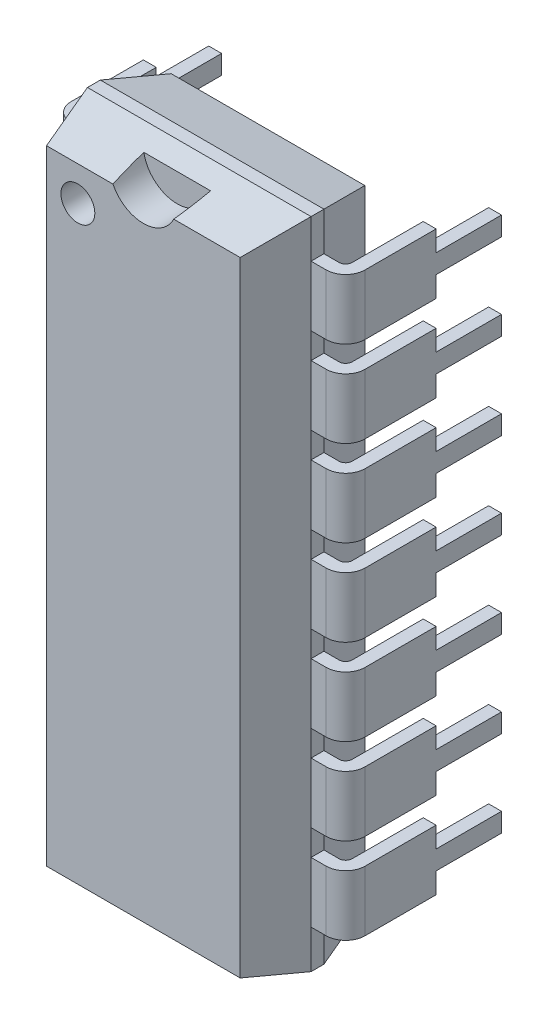
SolidWorks part; units mm, degrees
ref_plane "Спереди" through (0, 0, 0) normal (0, 0, 1) x (1, 0, 0)
ref_plane "Сверху" through (0, 0, 0) normal (0, 1, 0) x (1, 0, 0)
ref_plane "Справа" through (0, 0, 0) normal (1, 0, 0) x (0, 0, -1)
sketch "Эскиз1" plane through (0, 0, 0) normal (0, 0, 1) x (1, 0, 0)
  line L0 (8.07, 0.89) -> (8.07, -0.89) [skipped]
  line L1 (-0.19, 0.89) -> (0.19, 0.89)
  line L2 (-0.19, 0.89) -> (-0.19, -0.89)
  line L3 (-0.19, -0.89) -> (0.19, -0.89)
  line L4 (0.19, 0.89) -> (0.19, -0.89)
  line L5 (8.07, -0.89) -> (8.45, -0.89) [skipped]
  line L6 (8.45, 0.89) -> (8.45, -0.89) [skipped]
  line L7 (8.07, -1.65) -> (8.45, -1.65) [skipped]
  line L8 (-0.19, -1.65) -> (0.19, -1.65)
  line L9 (-0.19, -1.65) -> (-0.19, -3.43)
  line L10 (-0.19, -3.43) -> (0.19, -3.43)
  line L11 (0.19, -1.65) -> (0.19, -3.43)
  line L12 (8.07, -1.65) -> (8.07, -3.43) [skipped]
  line L13 (8.07, -3.43) -> (8.45, -3.43) [skipped]
  line L14 (8.45, -1.65) -> (8.45, -3.43) [skipped]
  line L15 (8.07, -4.19) -> (8.45, -4.19) [skipped]
  line L16 (-0.19, -4.19) -> (0.19, -4.19)
  line L17 (-0.19, -4.19) -> (-0.19, -5.97)
  line L18 (-0.19, -5.97) -> (0.19, -5.97)
  line L19 (0.19, -4.19) -> (0.19, -5.97)
  line L20 (8.07, -4.19) -> (8.07, -5.97) [skipped]
  line L21 (8.07, -5.97) -> (8.45, -5.97) [skipped]
  line L22 (8.45, -4.19) -> (8.45, -5.97) [skipped]
  line L23 (8.07, -6.73) -> (8.45, -6.73) [skipped]
  line L24 (-0.19, -6.73) -> (0.19, -6.73)
  line L25 (-0.19, -6.73) -> (-0.19, -8.51)
  line L26 (-0.19, -8.51) -> (0.19, -8.51)
  line L27 (0.19, -6.73) -> (0.19, -8.51)
  line L28 (8.07, -6.73) -> (8.07, -8.51) [skipped]
  line L29 (8.07, -8.51) -> (8.45, -8.51) [skipped]
  line L30 (8.45, -6.73) -> (8.45, -8.51) [skipped]
  line L31 (8.07, -9.27) -> (8.45, -9.27) [skipped]
  line L32 (-0.19, -9.27) -> (0.19, -9.27)
  line L33 (-0.19, -9.27) -> (-0.19, -11.05)
  line L34 (-0.19, -11.05) -> (0.19, -11.05)
  line L35 (0.19, -9.27) -> (0.19, -11.05)
  line L36 (8.07, -9.27) -> (8.07, -11.05) [skipped]
  line L37 (8.07, -11.05) -> (8.45, -11.05) [skipped]
  line L38 (8.45, -9.27) -> (8.45, -11.05) [skipped]
  line L39 (8.07, -11.81) -> (8.45, -11.81) [skipped]
  line L40 (-0.19, -11.81) -> (0.19, -11.81)
  line L41 (-0.19, -11.81) -> (-0.19, -13.59)
  line L42 (-0.19, -13.59) -> (0.19, -13.59)
  line L43 (0.19, -11.81) -> (0.19, -13.59)
  line L44 (8.07, -11.81) -> (8.07, -13.59) [skipped]
  line L45 (8.07, -13.59) -> (8.45, -13.59) [skipped]
  line L46 (8.45, -11.81) -> (8.45, -13.59) [skipped]
  line L47 (8.07, -14.35) -> (8.45, -14.35) [skipped]
  line L48 (-0.19, -14.35) -> (0.19, -14.35)
  line L49 (-0.19, -14.35) -> (-0.19, -16.13)
  line L50 (-0.19, -16.13) -> (0.19, -16.13)
  line L51 (0.19, -14.35) -> (0.19, -16.13)
  line L52 (8.07, -14.35) -> (8.07, -16.13) [skipped]
  line L53 (8.07, -16.13) -> (8.45, -16.13) [skipped]
  line L54 (8.45, -14.35) -> (8.45, -16.13) [skipped]
  line L56 (8.07, 0.89) -> (8.45, 0.89) [skipped]
ref_plane "Плоскость1" through (0, 0, 4.32) normal (0, 0, 1) x (1, 0, 0)
sketch "Эскиз2" plane through (0, 0, 4.32) normal (0, 0, 1) x (1, 0, 0)
  line L0 (4.13, 0.5264) -> (4.13, -12.1874) construction
  line L3 (-1.5963, -7.62) -> (10.5039, -7.62) construction
  line L7 (0.83, 2.03) -> (7.43, 2.03)
  line L8 (0.83, 2.03) -> (0.83, -17.27)
  line L9 (0.83, -17.27) -> (7.43, -17.27)
  line L10 (7.43, 2.03) -> (7.43, -17.27)
extrude "Вытянуть1" add sketch "Эскиз2" against normal blind 3.68
chamfer "Фаска1" distance 1.65 angle 15 8 edges at (4.13, -17.27, 0.64) (0.83, -7.62, 0.64) (4.13, 2.03, 0.64) (7.43, -7.62, 0.64) (4.13, -17.27, 4.32) (0.83, -7.62, 4.32) (4.13, 2.03, 4.32) (7.43, -7.62, 4.32)
sketch "Эскиз3" plane through (0, 0, 0) normal (0, 1, 0) x (1, 0, 0)
  line L0 (0, 0) -> (0, -2.1333)
  line L1 (0.3702, -2.48) -> (0.83, -2.48)
  line L2 (0.83, -2.29) -> (0.83, -2.67) construction
  arc A0 (0, -2.1333) -> (0.3702, -2.48) centre (0.3475, -2.1333) ccw
sweep "По траектории3" add profiles "Эскиз1" path "Эскиз3"
sketch "Эскиз4" plane through (0, 0, 0) normal (0, 0, 1) x (1, 0, 0)
  line L1 (8.07, 0.89) -> (8.45, 0.89)
  line L2 (8.07, 0.89) -> (8.07, -0.89)
  line L3 (8.07, -0.89) -> (8.45, -0.89)
  line L4 (8.45, 0.89) -> (8.45, -0.89)
  line L9 (8.07, -1.65) -> (8.45, -1.65)
  line L10 (8.07, -1.65) -> (8.07, -3.43)
  line L11 (8.07, -3.43) -> (8.45, -3.43)
  line L12 (8.45, -1.65) -> (8.45, -3.43)
  line L13 (8.07, -4.19) -> (8.45, -4.19)
  line L14 (8.07, -4.19) -> (8.07, -5.97)
  line L15 (8.07, -5.97) -> (8.45, -5.97)
  line L16 (8.45, -4.19) -> (8.45, -5.97)
  line L17 (8.07, -6.73) -> (8.45, -6.73)
  line L18 (8.07, -6.73) -> (8.07, -8.51)
  line L19 (8.07, -8.51) -> (8.45, -8.51)
  line L20 (8.45, -6.73) -> (8.45, -8.51)
  line L21 (8.07, -9.27) -> (8.45, -9.27)
  line L22 (8.07, -9.27) -> (8.07, -11.05)
  line L23 (8.07, -11.05) -> (8.45, -11.05)
  line L24 (8.45, -9.27) -> (8.45, -11.05)
  line L25 (8.07, -11.81) -> (8.45, -11.81)
  line L26 (8.07, -11.81) -> (8.07, -13.59)
  line L27 (8.07, -13.59) -> (8.45, -13.59)
  line L28 (8.45, -11.81) -> (8.45, -13.59)
  line L29 (8.07, -14.35) -> (8.45, -14.35)
  line L30 (8.07, -14.35) -> (8.07, -16.13)
  line L31 (8.07, -16.13) -> (8.45, -16.13)
  line L32 (8.45, -14.35) -> (8.45, -16.13)
sketch "Эскиз5" plane through (0, 0, 0) normal (0, 1, 0) x (1, 0, 0)
  line L0 (7.43, -2.48) -> (7.8737, -2.48)
  line L1 (7.43, -2.29) -> (7.43, -2.67) construction
  line L2 (8.26, -2.0937) -> (8.26, 0)
  line L3 (8.07, 0) -> (8.45, 0) construction
  arc A0 (7.8737, -2.48) -> (8.26, -2.0937) centre (7.8737, -2.0937) ccw
sweep "По траектории4" add profiles "Эскиз4" path "Эскиз5"
sketch "Эскиз6" plane through (0, 0, 4.32) normal (0, 0, 1) x (1, 0, 0)
  line L0 (0.83, 2.03) -> (7.43, 2.03) construction
  circle A0 centre (4.13, 2.03) radius 1
  circle A1 centre (2.1974, 0.5741) radius 0.5
extrude "Вырез-Вытянуть1" cut sketch "Эскиз6" against normal blind 1
sketch "Эскиз7" plane through (0, 0, 0) normal (0, 0, -1) x (-1, 0, 0)
  line L0 (-0.19, -0.89) -> (-0.19, 0.89) construction
  line L1 (-0.19, 0.28) -> (0.19, 0.28)
  line L2 (-0.19, 0.28) -> (-0.19, -0.28)
  line L3 (-0.19, -0.28) -> (0.19, -0.28)
  line L4 (0.19, 0.28) -> (0.19, -0.28)
  line L5 (-8.45, 0.28) -> (-8.07, 0.28)
  line L6 (-8.45, 0.28) -> (-8.45, -0.28)
  line L7 (-8.45, -0.28) -> (-8.07, -0.28)
  line L8 (-8.07, 0.28) -> (-8.07, -0.28)
  line L9 (-0.19, -2.26) -> (0.19, -2.26)
  line L10 (-0.19, -2.26) -> (-0.19, -2.82)
  line L11 (-0.19, -2.82) -> (0.19, -2.82)
  line L12 (0.19, -2.26) -> (0.19, -2.82)
  line L13 (-8.45, -2.26) -> (-8.07, -2.26)
  line L14 (-8.45, -2.26) -> (-8.45, -2.82)
  line L15 (-8.45, -2.82) -> (-8.07, -2.82)
  line L16 (-8.07, -2.26) -> (-8.07, -2.82)
  line L17 (-0.19, -4.8) -> (0.19, -4.8)
  line L18 (-0.19, -4.8) -> (-0.19, -5.36)
  line L19 (-0.19, -5.36) -> (0.19, -5.36)
  line L20 (0.19, -4.8) -> (0.19, -5.36)
  line L21 (-8.45, -4.8) -> (-8.07, -4.8)
  line L22 (-8.45, -4.8) -> (-8.45, -5.36)
  line L23 (-8.45, -5.36) -> (-8.07, -5.36)
  line L24 (-8.07, -4.8) -> (-8.07, -5.36)
  line L25 (-0.19, -7.34) -> (0.19, -7.34)
  line L26 (-0.19, -7.34) -> (-0.19, -7.9)
  line L27 (-0.19, -7.9) -> (0.19, -7.9)
  line L28 (0.19, -7.34) -> (0.19, -7.9)
  line L29 (-8.45, -7.34) -> (-8.07, -7.34)
  line L30 (-8.45, -7.34) -> (-8.45, -7.9)
  line L31 (-8.45, -7.9) -> (-8.07, -7.9)
  line L32 (-8.07, -7.34) -> (-8.07, -7.9)
  line L33 (-0.19, -9.88) -> (0.19, -9.88)
  line L34 (-0.19, -9.88) -> (-0.19, -10.44)
  line L35 (-0.19, -10.44) -> (0.19, -10.44)
  line L36 (0.19, -9.88) -> (0.19, -10.44)
  line L37 (-8.45, -9.88) -> (-8.07, -9.88)
  line L38 (-8.45, -9.88) -> (-8.45, -10.44)
  line L39 (-8.45, -10.44) -> (-8.07, -10.44)
  line L40 (-8.07, -9.88) -> (-8.07, -10.44)
  line L41 (-0.19, -12.42) -> (0.19, -12.42)
  line L42 (-0.19, -12.42) -> (-0.19, -12.98)
  line L43 (-0.19, -12.98) -> (0.19, -12.98)
  line L44 (0.19, -12.42) -> (0.19, -12.98)
  line L45 (-8.45, -12.42) -> (-8.07, -12.42)
  line L46 (-8.45, -12.42) -> (-8.45, -12.98)
  line L47 (-8.45, -12.98) -> (-8.07, -12.98)
  line L48 (-8.07, -12.42) -> (-8.07, -12.98)
  line L49 (-0.19, -14.96) -> (0.19, -14.96)
  line L50 (-0.19, -14.96) -> (-0.19, -15.52)
  line L51 (-0.19, -15.52) -> (0.19, -15.52)
  line L52 (0.19, -14.96) -> (0.19, -15.52)
  line L53 (-8.45, -14.96) -> (-8.07, -14.96)
  line L54 (-8.45, -14.96) -> (-8.45, -15.52)
  line L55 (-8.45, -15.52) -> (-8.07, -15.52)
  line L56 (-8.07, -14.96) -> (-8.07, -15.52)
  line L57 (-0.19, 0.28) -> (-8.45, 0.28) construction
  line L58 (-0.19, 0.28) -> (-0.19, -2.26) construction
extrude "Вытянуть2" add sketch "Эскиз7" along normal blind 3.43
sketch "Эскиз8" plane through (0, 0, -3.43) normal (0, 0, -1) x (-1, 0, 0)
  circle A0 centre (0, 0) radius 0.1072
extrude "Вырез-Вытянуть2" cut sketch "Эскиз8" against normal blind 3.5
sketch "Эскиз9" plane through (0, 0, -3.43) normal (0, 0, -1) x (-1, 0, 0)
  line L1 (-10.1311, -18.5245) -> (2.9836, -18.5245)
  line L2 (-10.1311, -18.5245) -> (-10.1311, 3.3138)
  line L3 (-10.1311, 3.3138) -> (2.9836, 3.3138)
  line L4 (2.9836, -18.5245) -> (2.9836, 3.3138)
extrude "Вырез-Вытянуть3" cut sketch "Эскиз9" against normal blind 1.5
